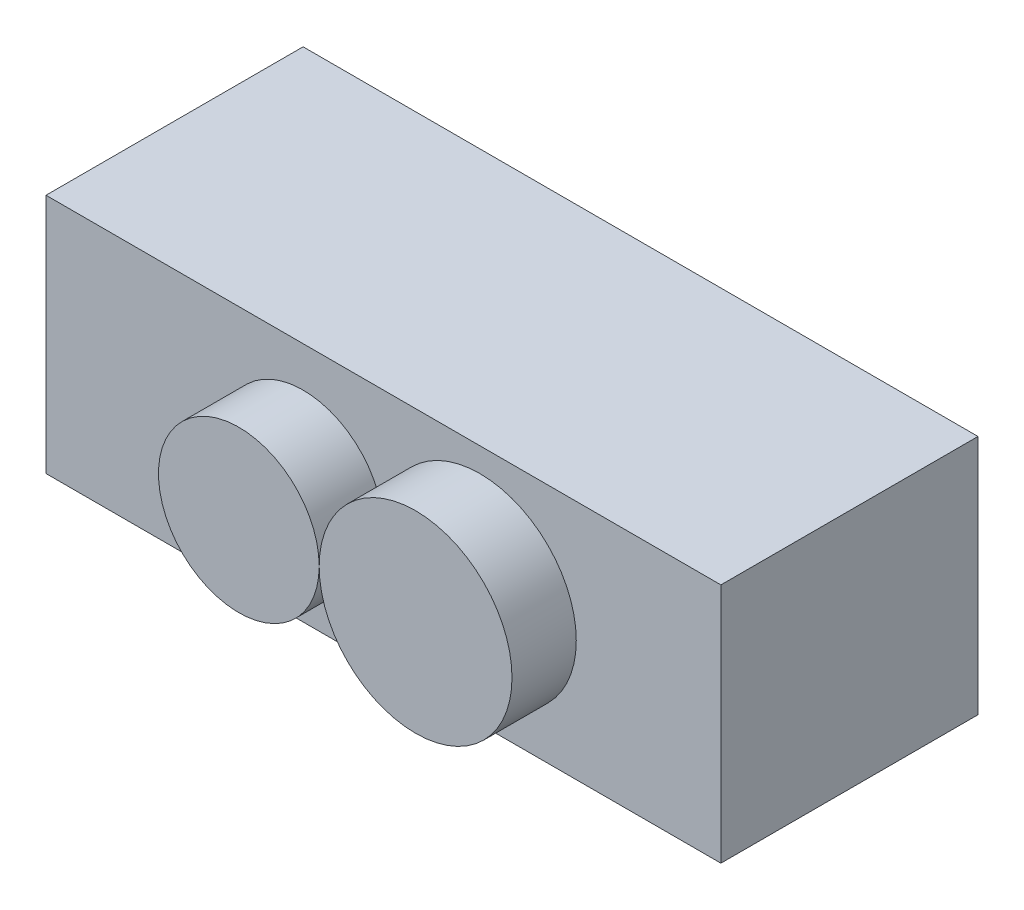
SolidWorks part; units mm, degrees
ref_plane "Front Plane" through (0, 0, 0) normal (0, 0, 1) x (1, 0, 0)
ref_plane "Top Plane" through (0, 0, 0) normal (0, 1, 0) x (1, 0, 0)
ref_plane "Right Plane" through (0, 0, 0) normal (1, 0, 0) x (0, 0, -1)
sketch "Sketch3" plane through (0, 0, 0) normal (0, 0, 1) x (1, 0, 0)
  line L1 (-21, -7.5) -> (21, -7.5)
  line L2 (-21, -7.5) -> (-21, 7.5)
  line L3 (-21, 7.5) -> (21, 7.5)
  line L4 (21, -7.5) -> (21, 7.5)
  line L5 (-21, -7.5) -> (21, 7.5) construction
  line L6 (-21, 7.5) -> (21, -7.5) construction
  point P0 (0, 0)
  dimension "D1" = 42
  dimension "D2" = 15
extrude "Boss-Extrude1" add sketch "Sketch3" along normal blind 16
sketch "Sketch4" plane through (0, 0, 16) normal (0, 0, 1) x (1, 0, 0)
  line L0 (0, 0) -> (-5, 0) construction
  line L1 (21, 7.5) -> (-21, 7.5) construction
  line L2 (0, 7.5) -> (0, -7.5) construction
  line L3 (-21, -7.5) -> (21, -7.5) construction
  line L4 (0, 0) -> (6, 0) construction
  circle A0 centre (-5, 0) radius 5
  circle A1 centre (6, 0) radius 6
  dimension "D1" = 5
  dimension "D2" = 6
extrude "Boss-Extrude4" add sketch "Sketch4" along normal blind 4 separate body contours A0 | A1
